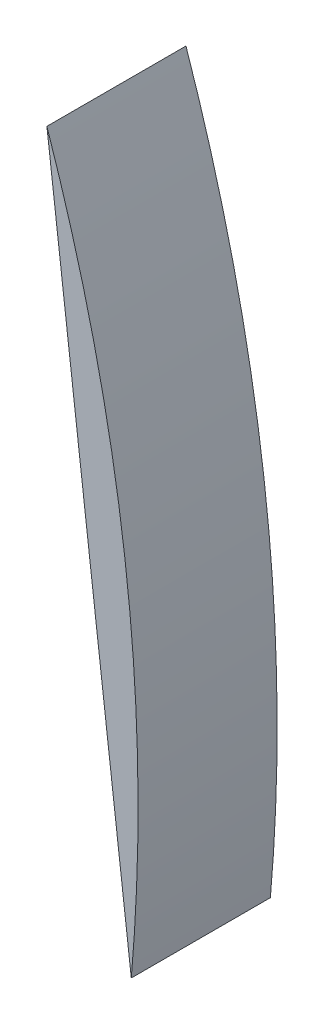
SolidWorks part; units mm, degrees
ref_plane "Front Plane" through (0, 0, 0) normal (0, 0, 1) x (1, 0, 0)
ref_plane "Top Plane" through (0, 0, 0) normal (0, 1, 0) x (1, 0, 0)
ref_plane "Right Plane" through (0, 0, 0) normal (1, 0, 0) x (0, 0, -1)
sketch "Sketch1" plane through (0, 0, 0) normal (0, 0, 1) x (1, 0, 0)
  line L0 (0, 0) -> (-60.6936, 500)
  spline S0 degree 2 poles (0, 0) (22.7091, 255.6208) (-60.6936, 500) knots 0 0 0 1 1 1
  dimension "D1" = 500
extrude "Boss-Extrude1" add sketch "Sketch1" along normal blind 100
